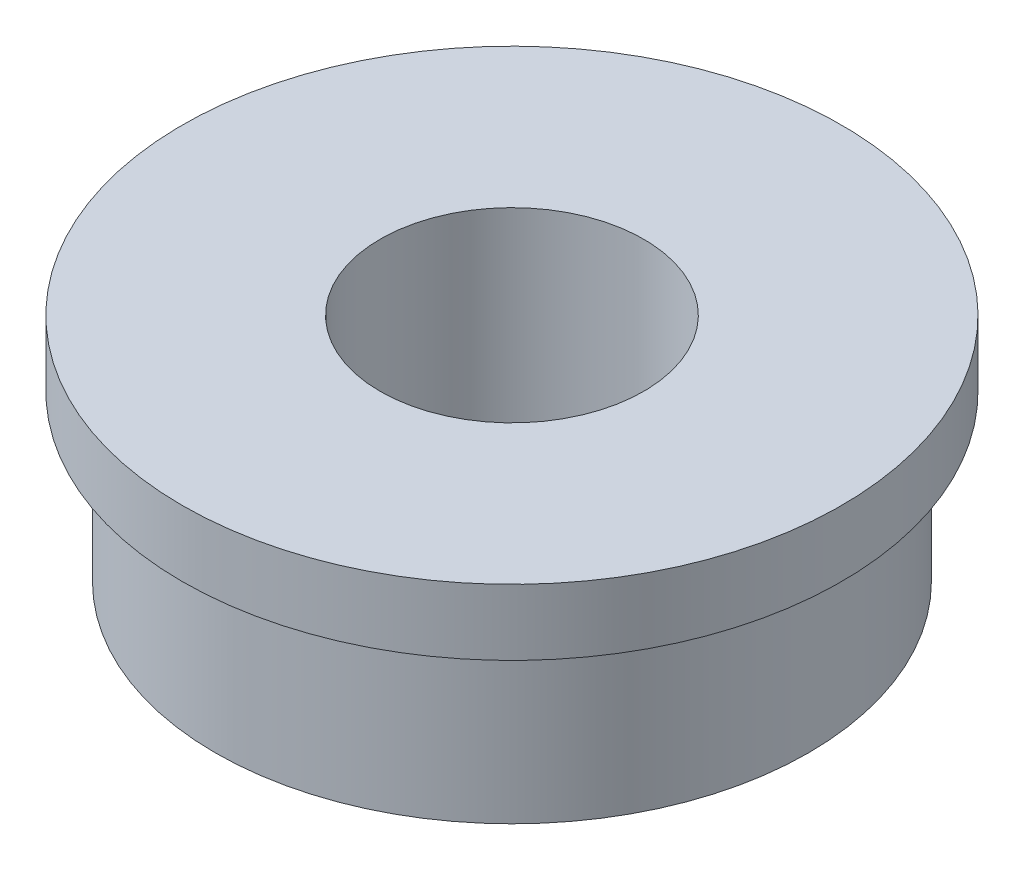
SolidWorks part; units mm, degrees
ref_plane "Front Plane" through (0, 0, 0) normal (0, 0, 1) x (1, 0, 0)
ref_plane "Top Plane" through (0, 0, 0) normal (0, 1, 0) x (1, 0, 0)
ref_plane "Right Plane" through (0, 0, 0) normal (1, 0, 0) x (0, 0, -1)
sketch "Sketch1" plane through (0, 0, 0) normal (0, 1, 0) x (1, 0, 0)
  circle A0 centre (0, 0) radius 14.2875
extrude "Boss-Extrude1" add sketch "Sketch1" along normal blind 11.1125
sketch "Sketch2" plane through (0, 11.1125, 0) normal (0, 1, 0) x (1, 0, 0)
  circle A0 centre (0, 0) radius 15.875
extrude "Boss-Extrude2" add sketch "Sketch2" against normal blind 3.175
sketch "Sketch3" plane through (0, 11.1125, 0) normal (0, 1, 0) x (1, 0, 0)
  circle A0 centre (0, 0) radius 6.35
extrude "Cut-Extrude1" cut sketch "Sketch3" against normal through all
